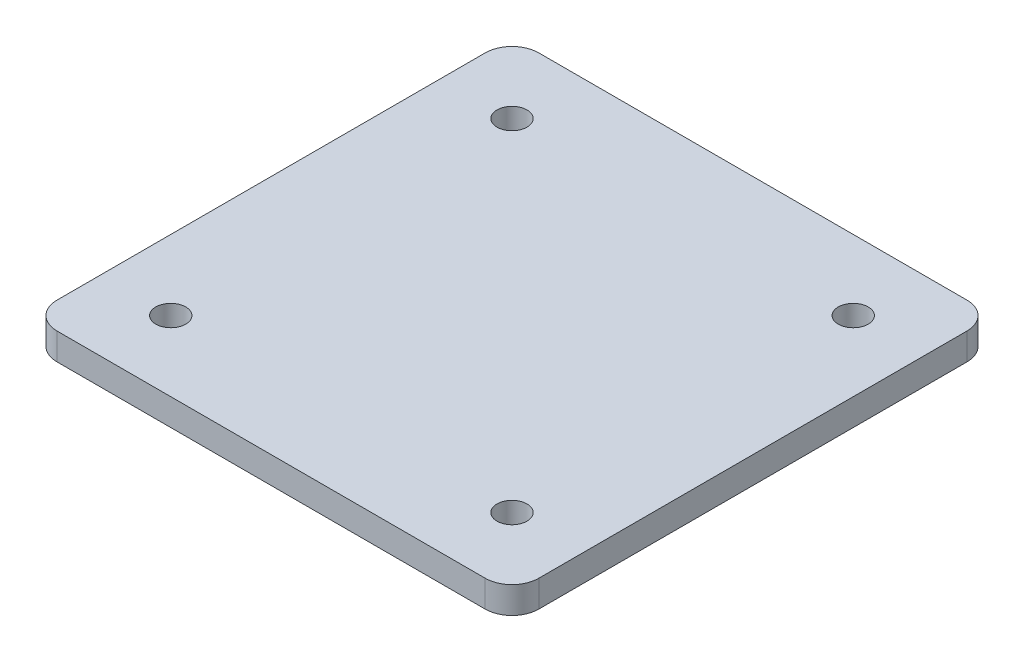
SolidWorks part; units mm, degrees
ref_plane "前视基准面" through (0, 0, 0) normal (0, 0, 1) x (1, 0, 0)
ref_plane "上视基准面" through (0, 0, 0) normal (0, 1, 0) x (1, 0, 0)
ref_plane "右视基准面" through (0, 0, 0) normal (1, 0, 0) x (0, 0, -1)
sketch "草图1" plane through (0, 0, 0) normal (0, 1, 0) x (1, 0, 0)
  line L1 (-18, 18) -> (18, 18)
  line L2 (-18, 18) -> (-18, -18)
  line L3 (-18, -18) -> (18, -18)
  line L4 (18, 18) -> (18, -18)
  line L5 (0, -18) -> (0, 18) construction
  line L6 (-18, 0) -> (18, 0) construction
  circle A0 centre (-12.75, 12.75) radius 1.1189
  circle A1 centre (12.75, 12.75) radius 1.1189
  circle A2 centre (12.75, -12.75) radius 1.1189
  circle A3 centre (-12.75, -12.75) radius 1.1189
  point P0 (0, 0)
  dimension "D3" = 25.5
  dimension "D4" = 25.5
  dimension "D1" = 36
  dimension "D2" = 36
extrude "凸台-拉伸1" add sketch "草图1" along normal blind 2
fillet "圆角1" radius 2 4 edges at (-18, 1, -18) (18, 1, -18) (-18, 1, 18) (18, 1, 18)
equation "\"m\"= 2"
